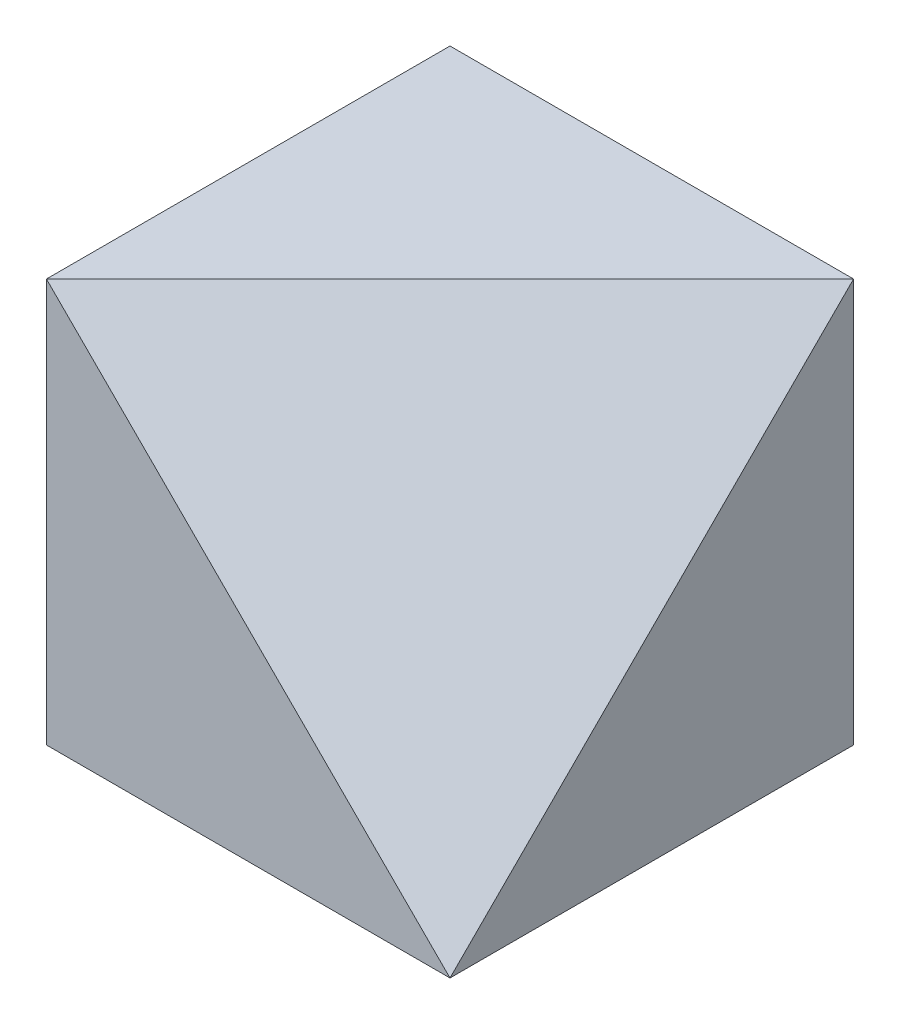
SolidWorks part; units mm, degrees
ref_plane "前基準面" through (0, 0, 0) normal (0, 0, 1) x (1, 0, 0)
ref_plane "上基準面" through (0, 0, 0) normal (0, 1, 0) x (1, 0, 0)
ref_plane "右基準面" through (0, 0, 0) normal (1, 0, 0) x (0, 0, -1)
sketch "草圖1" plane through (0, 0, 0) normal (0, 0, 1) x (1, 0, 0)
  line L1 (0, 0) -> (100, 0)
  line L2 (0, 0) -> (0, 100)
  line L3 (0, 100) -> (100, 100)
  line L4 (100, 0) -> (100, 100)
  dimension "D1" = 100
  dimension "D2" = 100
extrude "填料-伸長1" add sketch "草圖1" along normal blind 100
ref_plane "平面1" through (66.6667, 66.6667, 66.6667) normal (0.5774, 0.5774, 0.5774) x (0.8165, -0.4082, -0.4082)
sketch "草圖3" plane through (66.6667, 66.6667, 66.6667) normal (0.5774, 0.5774, 0.5774) x (0.8165, -0.4082, -0.4082)
  line L0 (-81.6497, 0) -> (40.8248, 70.7107)
  line L1 (40.8248, 70.7107) -> (40.8248, -70.7107)
  line L2 (40.8248, -70.7107) -> (-81.6497, 0)
extrude "除料-伸長1" cut sketch "草圖3" along normal through all
